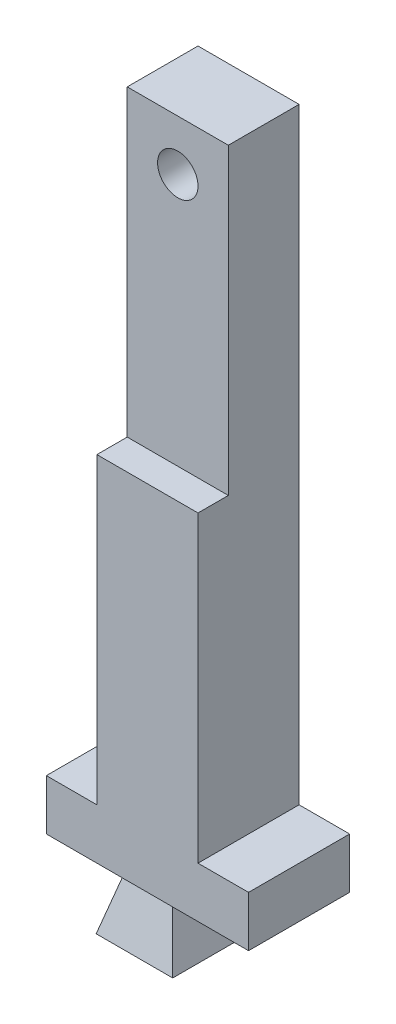
SolidWorks part; units mm, degrees
ref_plane "Front Plane" through (0, 0, 0) normal (0, 0, 1) x (1, 0, 0)
ref_plane "Top Plane" through (0, 0, 0) normal (0, 1, 0) x (1, 0, 0)
ref_plane "Right Plane" through (0, 0, 0) normal (1, 0, 0) x (0, 0, -1)
sketch "Sketch1" plane through (0, 0, 0) normal (0, 0, 1) x (1, 0, 0)
  line L0 (12.7, 0) -> (19.05, 0)
  line L1 (0, 0) -> (12.7, 0)
  line L2 (0, 6.35) -> (0, 44.45)
  line L3 (0, 44.45) -> (12.7, 44.45)
  line L4 (12.7, 6.35) -> (12.7, 44.45)
  line L5 (19.05, 0) -> (19.05, 6.35)
  line L6 (19.05, 6.35) -> (12.7, 6.35)
  line L7 (0, 0) -> (-6.35, 0)
  line L8 (-6.35, 0) -> (-6.35, 6.35)
  line L9 (-6.35, 6.35) -> (0, 6.35)
  dimension "D1" = 44.45
  dimension "D2" = 12.7
  dimension "D3" = 6.35
  dimension "D4" = 6.35
extrude "Boss-Extrude2" add sketch "Sketch1" along normal blind 12.7
sketch "Sketch2" plane through (0, 44.45, 0) normal (0, 1, 0) x (1, 0, 0)
  line L1 (0, 0) -> (12.7, 0)
  line L2 (0, 0) -> (0, -6.35)
  line L3 (0, -6.35) -> (12.7, -6.35)
  line L4 (12.7, 0) -> (12.7, -6.35)
  line L5 (12.7, -12.7) -> (12.7, 0) construction
  dimension "D1" = 6.35
  dimension "D2" = 12.7
extrude "Boss-Extrude3" add sketch "Sketch2" along normal blind 38.1
sketch "Sketch3" plane through (0, 0, 0) normal (0, -1, 0) x (1, 0, 0)
  line L6 (3.175, 0) -> (3.175, 12.7)
  line L7 (-6.35, 12.7) -> (19.05, 12.7) construction
  line L8 (3.175, 12.7) -> (9.525, 12.7)
  line L12 (9.525, 0) -> (9.525, 12.7)
  line L13 (9.525, 0) -> (3.175, 0)
extrude "Boss-Extrude5" add sketch "Sketch3" along normal blind 6.096 draft 15 draft outward yes
sketch "Sketch4" plane through (0, 0, 6.35) normal (0, 0, 1) x (1, 0, 0)
  line L1 (0, 44.45) -> (12.7, 44.45)
  line L2 (0, 44.45) -> (0, 82.55)
  line L3 (0, 82.55) -> (12.7, 82.55)
  line L4 (12.7, 44.45) -> (12.7, 82.55)
  dimension "D1" = 38.1
  dimension "D2" = 12.7
extrude "Boss-Extrude6" add sketch "Sketch4" along normal blind 2.54
sketch "Sketch5" plane through (0, 0, 8.89) normal (0, 0, 1) x (1, 0, 0)
  circle A0 centre (6.35, 76.2) radius 2.54
extrude "Cut-Extrude1" cut sketch "Sketch5" against normal blind 8.89
